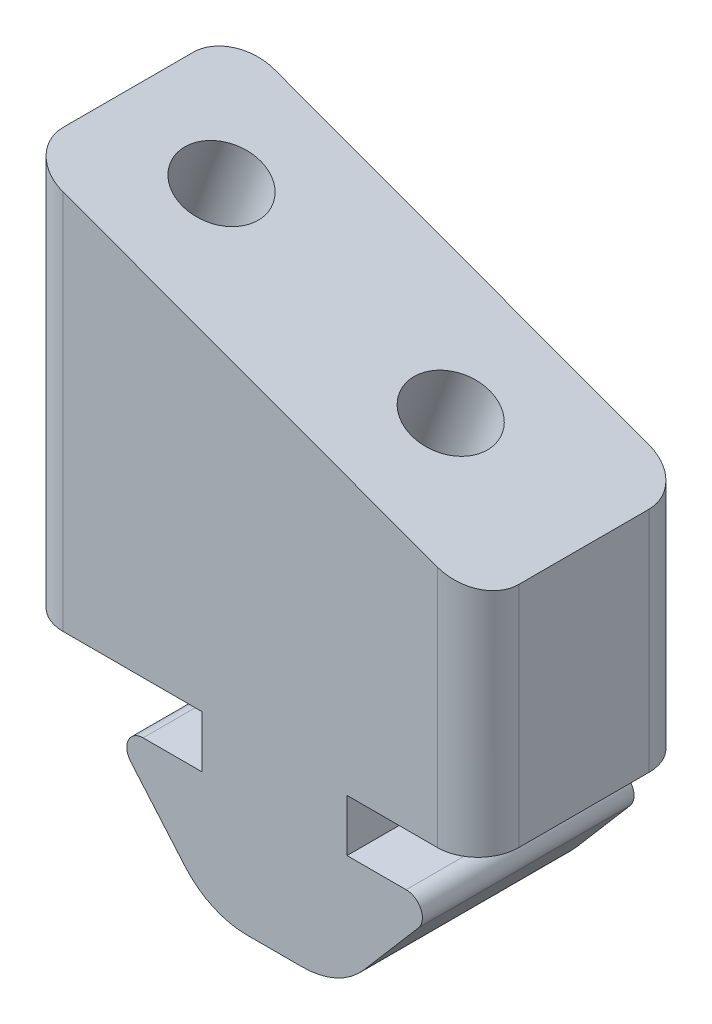
SolidWorks part; units mm, degrees
ref_plane "Front Plane" through (0, 0, 0) normal (0, 0, 1) x (1, 0, 0)
ref_plane "Top Plane" through (0, 0, 0) normal (0, 1, 0) x (1, 0, 0)
ref_plane "Right Plane" through (0, 0, 0) normal (1, 0, 0) x (0, 0, -1)
sketch "Sketch1" plane through (0, 0, 0) normal (0, 0, 1) x (1, 0, 0)
  line L0 (-4, 0) -> (4, 0)
  line L1 (4, 0) -> (10.25, 7.3)
  line L2 (10.25, 7.3) -> (4.45, 7.3)
  line L3 (4.45, 7.3) -> (4.45, 10.5)
  line L4 (4.45, 10.5) -> (-4.45, 10.5)
  line L5 (-4.45, 10.5) -> (-4.45, 7.3)
  line L6 (-4.45, 7.3) -> (-10.25, 7.3)
  line L7 (-10.25, 7.3) -> (-4, 0)
  line L8 (-12.5, 10.5) -> (-15.5, 10.5)
  line L9 (-12.5, 33.7) -> (12.5, 24.5)
  line L10 (-12.5, 33.7) -> (-12.5, 10.5)
  line L11 (-12.5, 10.5) -> (12.5, 10.5)
  line L12 (12.5, 24.5) -> (12.5, 10.5)
  line L13 (-15.5, 10.5) -> (-15.5, 34.804)
  line L14 (-15.5, 34.804) -> (-12.5, 33.7)
  point P0 (0, 10.5)
  point P3 (0, 23)
  point P4 (0, 0)
  point P17 (0, 29.1)
  point P18 (0, 23)
  dimension "D1" = 8
  dimension "D2" = 20.5
  dimension "D3" = 8.9
  dimension "D4" = 3.2
  dimension "D5" = 10.5
  dimension "D6" = 25
  dimension "D7" = 14
  dimension "D8" = 23.2
  dimension "D9" = 3
extrude "Boss-Extrude3" add sketch "Sketch1" along normal blind 13
fillet "Fillet1" radius 1 2 edges at (10.25, 7.3, 6.5) (-10.25, 7.3, 6.5)
fillet "Fillet2" radius 5 2 edges at (4, 0, 6.5) (-4, 0, 6.5)
sketch "Sketch2" plane through (9.4315, 25.6292, 0) normal (0.3454, 0.9385, 0) x (0.9385, -0.3454, 0)
  line L0 (-26.5661, -6.5) -> (3.2696, -6.5) construction
  line L2 (3.2696, -13) -> (3.2696, 0) construction
  line L4 (0.5499, -13) -> (0.5499, 0) construction
  line L5 (-26.5661, -13) -> (-26.5661, 0) construction
  circle A0 centre (-20.4501, -6.5) radius 2.4
  circle A1 centre (-5.4501, -6.5) radius 2.4
  point P10 (-23.3694, -6.5)
  dimension "D1" = 4.8
  dimension "D2" = 4.8
  dimension "D4" = 15
  dimension "D3" = 6
extrude "Cut-Extrude1" cut sketch "Sketch2" against normal blind 7.5
fillet "Fillet3" radius 2.5 4 edges at (12.5, 17.5, 0) (12.5, 17.5, 13) (-15.5, 22.652, 0) (-15.5, 22.652, 13)
equation "\"D1@Sketch2\"=\"D2@Sketch2\""
